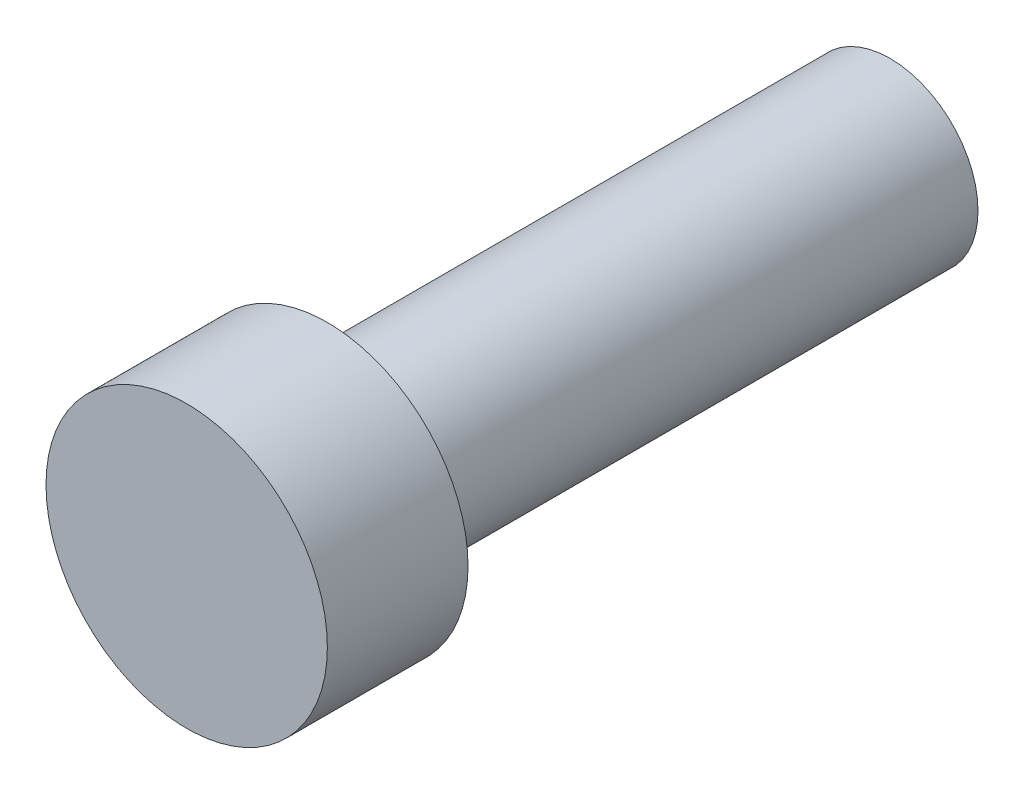
SolidWorks part; units mm, degrees
ref_plane "Front Plane" through (0, 0, 0) normal (0, 0, 1) x (1, 0, 0)
ref_plane "Top Plane" through (0, 0, 0) normal (0, 1, 0) x (1, 0, 0)
ref_plane "Right Plane" through (0, 0, 0) normal (1, 0, 0) x (0, 0, -1)
ref_plane "Plane1" through (0, 0, 0) normal (0, -1, 0) x (1, 0, 0)
sketch "Sketch1" plane through (0, 0, 0) normal (0, -1, 0) x (1, 0, 0)
  line L0 (5.08, 25.4) -> (0, 25.4)
  line L1 (0, 25.4) -> (0, 0)
  line L2 (0, 0) -> (3.175, 0)
  line L3 (3.175, 0) -> (3.175, 20.32)
  line L4 (3.175, 20.32) -> (5.08, 20.32)
  line L5 (5.08, 20.32) -> (5.08, 25.4)
  line L6 (0, 25.4) -> (0, 0) construction
  dimension "D1" = 3.175
  dimension "D2" = 5.08
  dimension "D3" = 25.4
  dimension "D4" = 5.08
revolve "Revolve1" add sketch "Sketch1" angle 360 about L6
